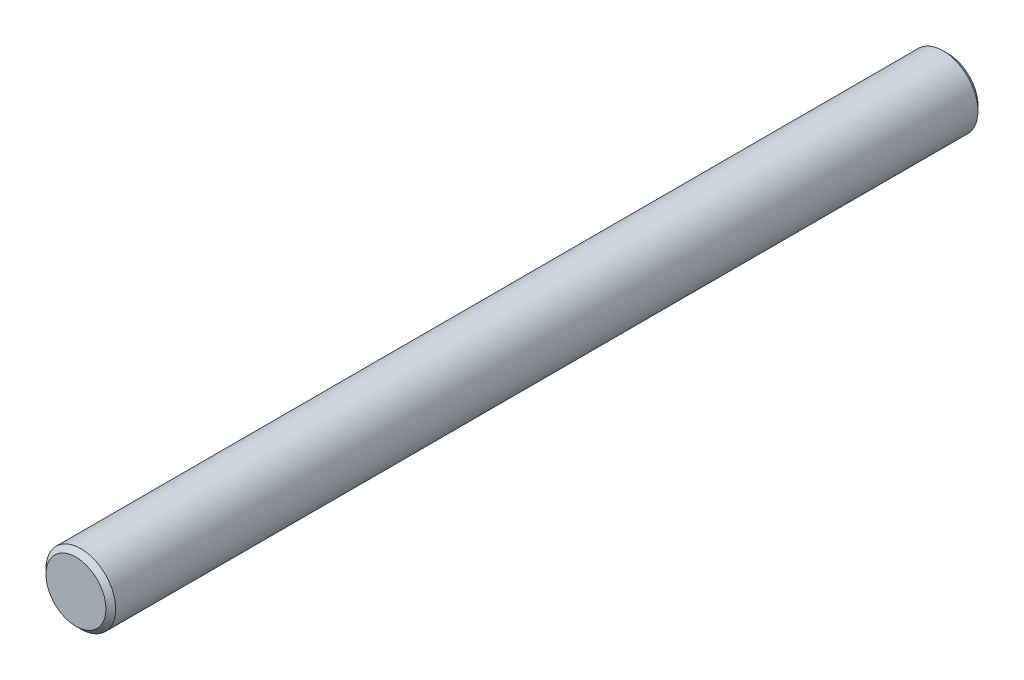
SolidWorks part; units mm, degrees
ref_plane "Front Plane" through (0, 0, 0) normal (0, 0, 1) x (1, 0, 0)
ref_plane "Top Plane" through (0, 0, 0) normal (0, 1, 0) x (1, 0, 0)
ref_plane "Right Plane" through (0, 0, 0) normal (1, 0, 0) x (0, 0, -1)
sketch "Sketch1" plane through (0, 0, 0) normal (0, 0, 1) x (1, 0, 0)
  line L0 (-4, 0) -> (4, 0) construction
  line L5 (0, 4) -> (0, -4) construction
  circle A1 centre (0, 0) radius 4
  point P7 (-4, 0)
  point P8 (4, 0)
  point P12 (0, -4)
  point P13 (0, 4)
  dimension "Diameter" = 8
sketch "Sketch2" plane through (0, 0, 0) normal (1, 0, 0) x (0, 0, -1)
  line L0 (-42, -4) -> (-42, 4) construction
  line L1 (50, -4) -> (-50, -4)
  line L2 (50, -4) -> (50, 4)
  line L3 (50, 4) -> (-50, 4)
  line L4 (-50, -4) -> (-50, 4)
  line L5 (50, -4) -> (-50, 4) construction
  line L6 (50, 4) -> (-50, -4) construction
  line L7 (42, -4) -> (42, 4) construction
  line L8 (-50, 3.44) -> (-49.44, 4) construction
  point P0 (0, 0)
  point P8 (-50, 4)
  point P9 (50, 4)
  point P14 (-42, 4)
  point P15 (-42, -4)
  point P16 (42, 4)
  point P17 (42, -4)
  point P25 (0, -4)
  dimension "Length" = 100
  dimension "D1" = 8
  dimension "D2" = 8
  dimension "Chamfer Typ," = 45
  dimension "D4" = 0.56
sketch "Sketch3" plane through (0, 0, 0) normal (0, 0, 1) x (1, 0, 0)
  circle A0 centre (0, 0) radius 4 construction
  circle A1 centre (0, 0) radius 4
extrude "Boss-Extrude1" add sketch "Sketch3" along normal up to vertex (50 mm away) and the other way up to vertex (50 mm away) up to point (0, 4, 50) other way up to point (0, 4, -50)
chamfer "Chamfer1" distance 0.56 angle 45 2 edges at (4, 0, -50) (4, 0, 50)
equation "\"D1@Sketch2\"=\"Diameter@Sketch1\""
equation "\"D2@Sketch2\"=\"Diameter@Sketch1\""
equation "\"D1@Chamfer1\"=\"Diameter@Sketch1\"*.07"
equation "\"D4@Sketch2\"=\"Diameter@Sketch1\"*.07"
equation "\"D2@Chamfer1\"=\"Chamfer Typ,@Sketch2\""
